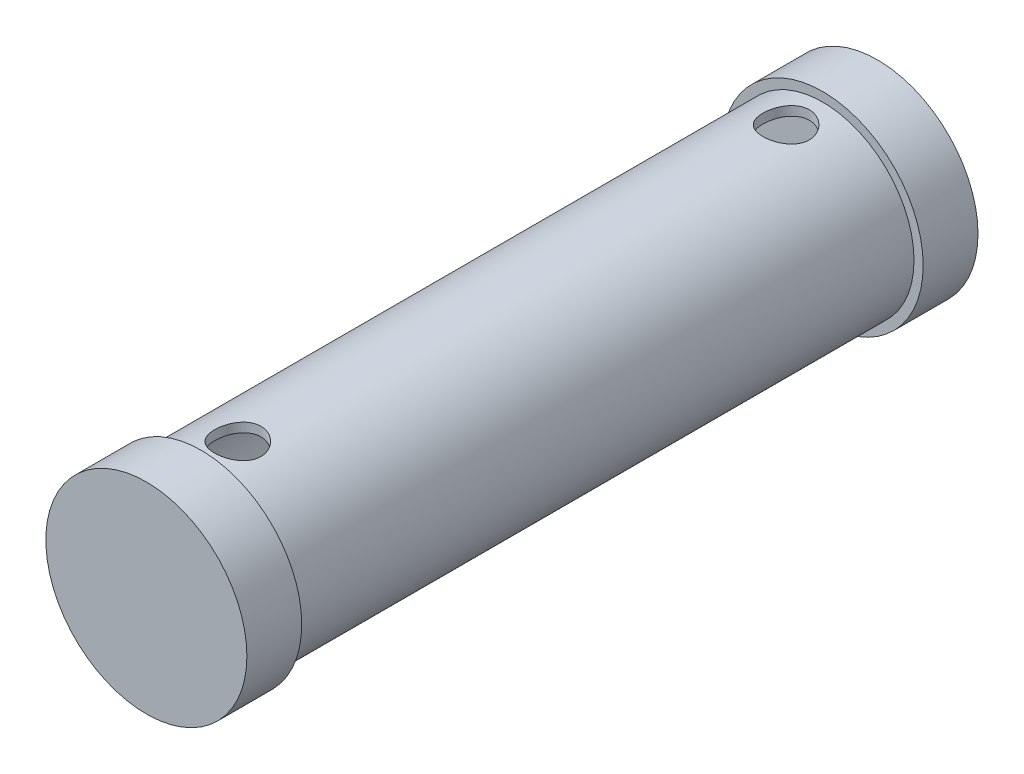
SolidWorks part; units mm, degrees
ref_plane "Alzado" through (0, 0, 0) normal (0, 0, 1) x (1, 0, 0)
ref_plane "Planta" through (0, 0, 0) normal (0, 1, 0) x (1, 0, 0)
ref_plane "Vista lateral" through (0, 0, 0) normal (1, 0, 0) x (0, 0, -1)
sketch "Croquis1" plane through (0, 0, 0) normal (0, 0, 1) x (1, 0, 0)
  circle A0 centre (0, 0) radius 50
  circle A1 centre (0, 0) radius 45
extrude "Saliente-Extruir1" add sketch "Croquis1" along normal blind 400
sketch "Croquis2" plane through (0, 0, 0) normal (0, 0, 1) x (1, 0, 0)
  circle A1 centre (0, 0) radius 55
extrude "Saliente-Extruir2" add sketch "Croquis2" along normal blind 30
ref_plane "Plano1" through (0, 0, 400) normal (0, 0, 1) x (1, 0, 0)
sketch "Croquis3" plane through (0, 0, 400) normal (0, 0, 1) x (1, 0, 0)
  circle A0 centre (0, 0) radius 55
extrude "Saliente-Extruir3" add sketch "Croquis3" against normal blind 30
ref_plane "Plano2" through (0, 50, 0) normal (0, 1, 0) x (1, 0, 0)
sketch "Croquis5" plane through (0, 50, 0) normal (0, 1, 0) x (1, 0, 0)
  circle A3 centre (0, -350) radius 12.7
  circle A4 centre (0, -50) radius 12.7
extrude "Cortar-Extruir2" cut sketch "Croquis5" against normal blind 60
ref_plane "Plano3" through (0, -50, 0) normal (0, 1, 0) x (1, 0, 0)
sketch "Croquis7" plane through (0, 0, 0) normal (1, 0, 0) x (0, 0, -1)
  circle A0 centre (-200, 0) radius 12.7
extrude "Cortar-Extruir4" cut sketch "Croquis7" against normal blind 106
